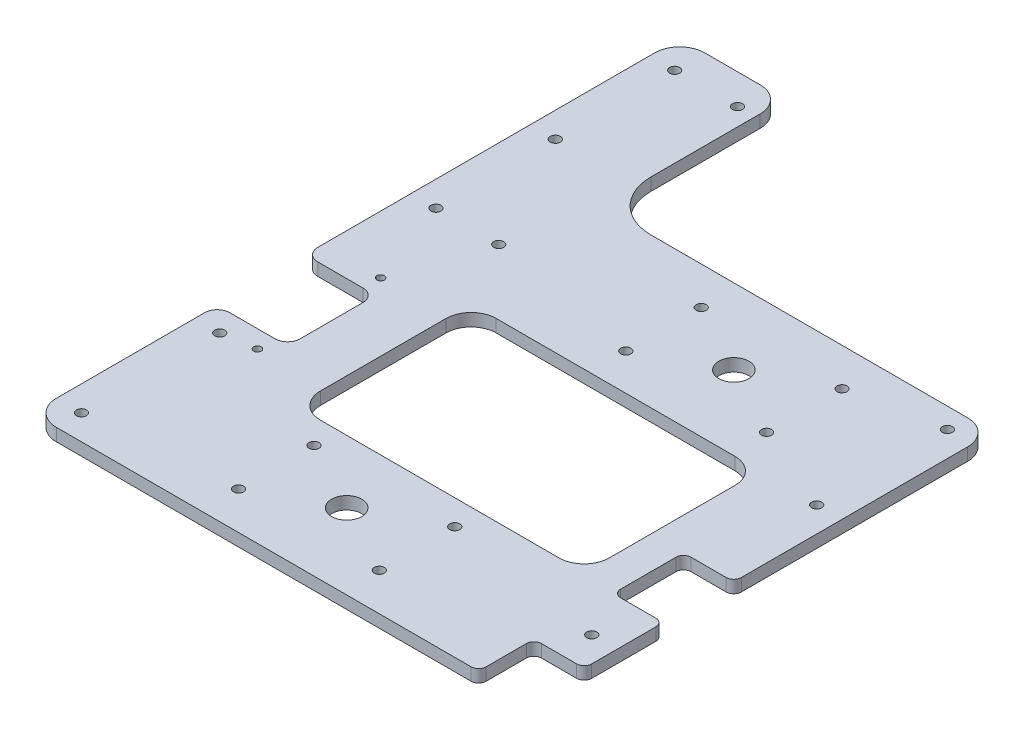
SolidWorks part; units mm, degrees
ref_plane "前视基准面" through (0, 0, 0) normal (0, 0, 1) x (1, 0, 0)
ref_plane "上视基准面" through (0, 0, 0) normal (0, 1, 0) x (1, 0, 0)
ref_plane "右视基准面" through (0, 0, 0) normal (1, 0, 0) x (0, 0, -1)
sketch "草图1" plane through (0, 0, 0) normal (0, 1, 0) x (1, 0, 0)
  line L1 (106.5, -95) -> (-106.5, -95)
  line L2 (106.5, -95) -> (106.5, 95)
  line L3 (106.5, 95) -> (-106.5, 95)
  line L4 (-106.5, -95) -> (-106.5, 95)
  line L5 (106.5, -95) -> (-106.5, 95) construction
  line L6 (106.5, 95) -> (-106.5, -95) construction
  point P0 (0, 0)
  dimension "D1" = 213
  dimension "D2" = 190
extrude "凸台-拉伸1" add sketch "草图1" along normal blind 5
sketch "草图2" plane through (0, 5, 0) normal (0, 1, 0) x (1, 0, 0)
  line L2 (106.5, 95) -> (-106.5, 95) construction
  line L4 (-106.5, 95) -> (-106.5, -95) construction
  circle A0 centre (-9.5, 80) radius 2
  circle A1 centre (46.5, 80) radius 2
  circle A2 centre (-9.5, 50) radius 2
  circle A3 centre (46.5, 50) radius 2
  circle A4 centre (-39, -44.5542) radius 2
  circle A5 centre (17, -44.5542) radius 2
  circle A6 centre (17, -74.5542) radius 2
  circle A7 centre (-39, -74.5542) radius 2
  circle A8 centre (-11, -59.5542) radius 6
  circle A9 centre (18.5, 65) radius 6
  dimension "D2" = 28
  dimension "D3" = 56
  dimension "D4" = 56
  dimension "D5" = 15
  dimension "D6" = 30
  dimension "D7" = 15
  dimension "D8" = 30
  dimension "D9" = 4
  dimension "D10" = 4
  dimension "D11" = 4
  dimension "D12" = 4
  dimension "D13" = 4
  dimension "D14" = 4
  dimension "D15" = 4
  dimension "D16" = 4
  dimension "D17" = 56
  dimension "D18" = 56
  dimension "D19" = 30
  dimension "D20" = 30
  dimension "D21" = 28
  dimension "D22" = 15
  dimension "D23" = 12
  dimension "D24" = 12
  dimension "D25" = 30
  dimension "D26" = 95.5
  dimension "D27" = 128
  dimension "D28" = 125
  dimension "D29" = 28
  dimension "D30" = 28
  dimension "D31" = 15
extrude "切除-拉伸1" cut sketch "草图2" against normal through all
sketch "草图3" plane through (0, 5, 0) normal (0, 1, 0) x (1, 0, 0)
  line L0 (-106.5, -89.5542) -> (106.5, -89.5542)
  line L1 (-106.5, 95) -> (-106.5, -95) construction
  line L2 (106.5, -95) -> (106.5, 95) construction
  line L3 (106.5, -89.5542) -> (106.5, -95)
  line L4 (106.5, -95) -> (-106.5, -95)
  line L5 (-106.5, -95) -> (-106.5, -89.5542)
  circle A0 centre (-11, -59.5542) radius 6 construction
  dimension "D1" = 30
extrude "切除-拉伸2" cut sketch "草图3" against normal through all
sketch "草图4" plane through (0, 5, 0) normal (0, 1, 0) x (1, 0, 0)
  line L0 (-106.5, 19.4458) -> (-78.5, 19.4458)
  line L1 (-106.5, 95) -> (-106.5, -89.5542) construction
  line L2 (-78.5, 19.4458) -> (-78.5, -15.5542)
  line L3 (-78.5, -15.5542) -> (-106.5, -15.5542)
  line L4 (-106.5, -15.5542) -> (-106.5, 19.4458)
  line L5 (106.5, -89.5542) -> (-106.5, -89.5542) construction
  dimension "D1" = 74
  dimension "D2" = 109
  dimension "D3" = 28
extrude "切除-拉伸3" cut sketch "草图4" against normal through all
fillet "圆角1" radius 5 4 edges at (-106.5, 2.5, 15.5542) (-78.5, 2.5, 15.5542) (-78.5, 2.5, -19.4458) (-106.5, 2.5, -19.4458)
sketch "草图5" plane through (0, 5, 0) normal (0, 1, 0) x (1, 0, 0)
  line L0 (-106.5, 95) -> (-106.5, 168.4458)
  line L1 (-106.5, 168.4458) -> (-64.5, 168.4458)
  line L2 (-64.5, 168.4458) -> (-64.5, 95)
  line L3 (106.5, 95) -> (-106.5, 95) construction
  line L4 (-106.5, 95) -> (-64.5, 95)
  line L5 (106.5, -89.5542) -> (-106.5, -89.5542) construction
  dimension "D1" = 258
  dimension "D2" = 42
extrude "凸台-拉伸2" add sketch "草图5" against normal blind 5
fillet "圆角2" radius 20 1 edges at (-64.5, 2.5, -95)
sketch "草图6" plane through (0, 5, 0) normal (0, 1, 0) x (1, 0, 0)
  line L0 (-64.5, 168.4458) -> (-106.5, 168.4458) construction
  line L1 (-106.5, 168.4458) -> (-106.5, 24.4458) construction
  circle A0 centre (-96.5, 156.4458) radius 2
  circle A1 centre (-71.5, 156.4458) radius 2
  circle A2 centre (-71.5, 61.4458) radius 2
  circle A3 centre (-96.5, 61.4458) radius 2
  dimension "D1" = 12
  dimension "D2" = 12
  dimension "D3" = 4
  dimension "D4" = 10
  dimension "D5" = 25
  dimension "D6" = 10
  dimension "D7" = 25
  dimension "D8" = 95
  dimension "D9" = 95
  dimension "D10" = 4
  dimension "D11" = 4
  dimension "D12" = 4
extrude "切除-拉伸4" cut sketch "草图6" against normal through all
sketch "草图7" plane through (0, 5, 0) normal (0, 1, 0) x (1, 0, 0)
  line L0 (-106.5, 168.4458) -> (-106.5, 24.4458) construction
  line L1 (-106.5, -20.5542) -> (-106.5, -89.5542) construction
  line L2 (106.5, -89.5542) -> (106.5, 95) construction
  line L3 (106.5, -89.5542) -> (-106.5, -89.5542) construction
  circle A0 centre (-96.5, 108.9458) radius 2
  circle A1 centre (-96.5, -24.5542) radius 2
  circle A2 centre (-96.5, -79.5542) radius 2
  circle A6 centre (81.5, 86.9458) radius 2
  circle A7 centre (81.5, 34.9458) radius 2
  circle A8 centre (81.5, -54.5542) radius 2
  dimension "D1" = 10
  dimension "D2" = 10
  dimension "D3" = 10
  dimension "D7" = 25
  dimension "D8" = 25
  dimension "D9" = 25
  dimension "D10" = 10
  dimension "D11" = 65
  dimension "D12" = 198.5
  dimension "D13" = 35
  dimension "D15" = 124.5
  dimension "D18" = 176.5
  dimension "D19" = 4
  dimension "D21" = 4
  dimension "D23" = 4
  dimension "D25" = 4
  dimension "D26" = 4
  dimension "D27" = 4
extrude "切除-拉伸5" cut sketch "草图7" against normal through all
sketch "草图8" plane through (0, 5, 0) normal (0, 1, 0) x (1, 0, 0)
  line L0 (71.5, -89.5542) -> (71.5, -67.5542)
  line L1 (106.5, -89.5542) -> (-106.5, -89.5542) construction
  line L2 (71.5, -67.5542) -> (91.5, -67.5542)
  line L3 (91.5, -67.5542) -> (91.5, -89.5542)
  line L4 (91.5, -89.5542) -> (71.5, -89.5542)
  line L5 (71.5, -36.0542) -> (71.5, -8.0542)
  line L6 (71.5, -8.0542) -> (91.5, -8.0542)
  line L7 (91.5, -8.0542) -> (91.5, -36.0542)
  line L8 (91.5, -36.0542) -> (71.5, -36.0542)
  line L9 (106.5, -89.5542) -> (106.5, 95) construction
  point P8 (81.5, -36.0542)
  dimension "D1" = 22
  dimension "D2" = 53.5
  dimension "D3" = 28
  dimension "D4" = 15
  dimension "D5" = 20
  dimension "D6" = 15
extrude "切除-拉伸6" cut sketch "草图8" against normal through all
fillet "圆角3" radius 3 6 edges at (71.5, 2.5, 89.5542) (91.5, 2.5, 89.5542) (91.5, 2.5, 67.5542) (71.5, 2.5, 67.5542) (71.5, 2.5, 36.0542) (71.5, 2.5, 8.0542)
sketch "草图9" plane through (0, 5, 0) normal (0, 1, 0) x (1, 0, 0)
  line L0 (88.5, -67.5542) -> (106.5, -67.5542)
  line L1 (106.5, -89.5542) -> (106.5, 95) construction
  line L2 (106.5, -67.5542) -> (106.5, -89.5542)
  line L3 (106.5, -89.5542) -> (88.5, -89.5542)
  line L4 (88.5, -89.5542) -> (88.5, -67.5542)
extrude "切除-拉伸7" cut sketch "草图9" against normal through all
sketch "草图10" plane through (0, 5, 0) normal (0, 1, 0) x (1, 0, 0)
  line L0 (68.5, -89.5542) -> (-106.5, -89.5542) construction
  line L1 (-106.5, -20.5542) -> (-106.5, -89.5542) construction
  line L2 (-106.5, 168.4458) -> (-106.5, 24.4458) construction
  circle A0 centre (-83.5, 26.4458) radius 1.5
  circle A1 centre (-83.5, -22.5542) radius 1.5
  dimension "D1" = 67
  dimension "D2" = 23
  dimension "D3" = 23
  dimension "D4" = 49
  dimension "D5" = 3
  dimension "D6" = 3
extrude "切除-拉伸8" cut sketch "草图10" against normal through all
fillet "圆角4" radius 10 5 edges at (106.5, 2.5, 67.5542) (-106.5, 2.5, 89.5542) (-106.5, 2.5, -168.4458) (-64.5, 2.5, -168.4458) (106.5, 2.5, -95)
sketch "草图11" plane through (0, 5, 0) normal (0, 1, 0) x (1, 0, 0)
  line L0 (-56.5, 35.4458) -> (58.5, 35.4458)
  line L1 (58.5, 35.4458) -> (58.5, -34.5542)
  line L2 (58.5, -34.5542) -> (-56.5, -34.5542)
  line L3 (-56.5, -34.5542) -> (-56.5, 35.4458)
  line L4 (-106.5, 158.4458) -> (-106.5, 24.4458) construction
  line L5 (68.5, -89.5542) -> (-96.5, -89.5542) construction
  dimension "D1" = 50
  dimension "D2" = 55
  dimension "D3" = 125
  dimension "D4" = 115
extrude "切除-拉伸9" cut sketch "草图11" against normal through all
fillet "圆角5" radius 10 4 edges at (58.5, 2.5, 34.5542) (-56.5, 2.5, 34.5542) (58.5, 2.5, -35.4458) (-56.5, 2.5, -35.4458)
sketch "草图12" plane through (0, 5, 0) normal (0, 1, 0) x (1, 0, 0)
  line L0 (91.5, 95) -> (91.5, -67.5542)
  line L1 (96.5, 95) -> (-44.5, 95) construction
  line L2 (96.5, -67.5542) -> (74.5, -67.5542) construction
  line L3 (91.5, -67.5542) -> (111.4935, -67.5542)
  line L4 (111.4935, -67.5542) -> (111.4935, 95)
  line L5 (111.4935, 95) -> (91.5, 95)
  circle A0 centre (81.5, 34.9458) radius 2 construction
  dimension "D1" = 10
extrude "切除-拉伸10" cut sketch "草图12" against normal through all
fillet "圆角6" radius 3 3 edges at (91.5, 2.5, 36.0542) (91.5, 2.5, 67.5542) (91.5, 2.5, 8.0542)
fillet "圆角7" radius 10 1 edges at (91.5, 2.5, -95)
